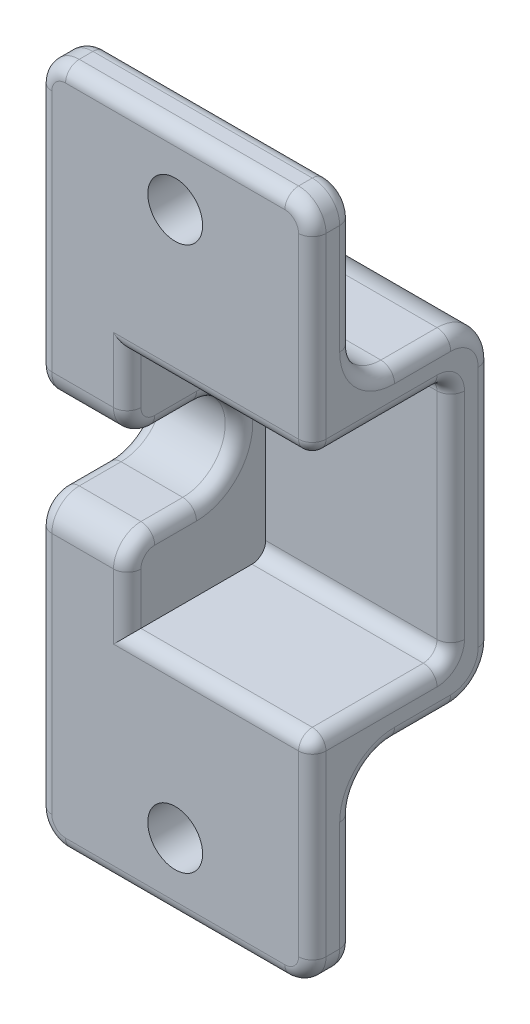
SolidWorks part; units mm, degrees
ref_plane "Front Plane" through (0, 0, 0) normal (0, 0, 1) x (1, 0, 0)
ref_plane "Top Plane" through (0, 0, 0) normal (0, 1, 0) x (1, 0, 0)
ref_plane "Right Plane" through (0, 0, 0) normal (1, 0, 0) x (0, 0, -1)
sketch "Sketch1" plane through (0, 0, 0) normal (1, 0, 0) x (0, 0, -1)
  line L0 (0, 0) -> (3, 0)
  line L1 (3, 0) -> (3, 13)
  line L2 (3, 13) -> (13.1, 13)
  line L3 (13.1, 13) -> (13.1, 36.7)
  line L4 (13.1, 36.7) -> (3, 36.7)
  line L5 (3, 36.7) -> (3, 49.7)
  line L6 (3, 49.7) -> (0, 49.7)
  line L7 (0, 49.7) -> (0, 33.7)
  line L8 (0, 33.7) -> (10.1, 33.7)
  line L9 (10.1, 33.7) -> (10.1, 16)
  line L10 (10.1, 16) -> (0, 16)
  line L11 (0, 16) -> (0, 0)
  point P10 (23.8643, 8.2791)
  point P14 (5.3757, 11.8085)
  dimension "D1" = 17.7
  dimension "D2" = 10.1
  dimension "D3" = 3
  dimension "D4" = 3
  dimension "D5" = 13
  dimension "D6" = 3
extrude "Boss-Extrude1" add sketch "Sketch1" along normal blind 13.5
sketch "Sketch2" plane through (0, 0, 0) normal (-1, 0, 0) x (0, 0, 1)
  line L0 (0, 0) -> (-3, 0)
  line L1 (-3, 0) -> (-3, 13)
  line L2 (-3, 13) -> (-13.1, 13)
  line L3 (-13.1, 13) -> (-13.1, 36.7) construction
  line L4 (-3, 13) -> (-13.1, 13) construction
  line L5 (-13.1, 13) -> (-13.1, 36.7)
  line L6 (-13.1, 36.7) -> (-3, 36.7)
  line L7 (-3, 36.7) -> (-3, 49.7)
  line L8 (-3, 49.7) -> (0, 49.7)
  line L9 (0, 49.7) -> (0, 27.95)
  line L10 (0, 27.95) -> (-5.05, 27.95)
  line L11 (0, 0) -> (0, 21.75)
  line L12 (0, 21.75) -> (-5.05, 21.75)
  line L13 (0, 21.75) -> (0, 27.95) construction
  line L14 (0, 24.85) -> (-10.1, 24.85) construction
  line L15 (-10.1, 33.7) -> (-10.1, 16) construction
  arc A0 (-5.05, 21.75) -> (-5.05, 27.95) centre (-5.05, 24.85) cw
  point P28 (0, 0)
  dimension "D1" = 3.1
extrude "Boss-Extrude2" add sketch "Sketch2" along normal blind 6.5
fillet "Fillet1" radius 3 4 edges at (3.5, 13, -13.1) (3.5, 13, -3) (3.5, 36.7, -13.1) (3.5, 36.7, -3)
fillet "Fillet2" radius 2 6 edges at (13.5, 0, -1.5) (-6.5, 0, -1.5) (-6.5, 49.7, -1.5) (13.5, 49.7, -1.5) (-3.25, 21.75, 0) (-3.25, 27.95, 0)
sketch "Sketch3" plane through (0, 0, -3) normal (0, 0, -1) x (-1, 0, 0)
  line L0 (-3.5, 44.7) -> (-3.5, 5) construction
  line L1 (-3.5, 5) -> (-3.5, 0) construction
  line L2 (-11.5, 0) -> (4.5, 0) construction
  line L3 (-3.5, 44.7) -> (-3.5, 49.7) construction
  line L4 (-11.5, 49.7) -> (4.5, 49.7) construction
  circle A0 centre (-3.5, 5) radius 2
  circle A1 centre (-3.5, 44.7) radius 2
  point P4 (-3, 4.2036)
  dimension "D1" = 4
  dimension "D2" = 5
extrude "Cut-Extrude1" cut sketch "Sketch3" against normal up to surface (3 mm away) up to face at (2.625, 9.3339, 0)
fillet "Fillet3" radius 1 53 edges at (13.5, 9, 0) (12.9142, 0.5858, 0) (3.5, 0, 0) (-5.9142, 0.5858, 0) (-6.5, 10.875, 0) (-6.5, 21.1642, -0.5858) (-6.5, 21.75, -3.525) (-6.5, 24.85, -8.15) (-6.5, 27.95, -3.525) (-6.5, 28.5358, -0.5858) (13.5, 40.7, 0) (12.9142, 49.1142, 0) (3.5, 49.7, 0) (-5.9142, 49.1142, 0) (0, 17.875, 0) (0, 21.1642, -0.5858) (0, 21.75, -3.525) (0, 31.825, 0) (0, 28.5358, -0.5858) (0, 27.95, -3.525) (-6.5, 38.825, 0) (0, 24.85, -8.15) (6.75, 33.7, -10.1) (6.75, 16, 0) (6.75, 16, -10.1) (6.75, 33.7, 0) (13.5, 13.8787, -12.2213) (13.5, 13, -8.05) (13.5, 12.1213, -3.8787) (13.5, 6, -3) (12.9142, 0.5858, -3) (3.5, 0, -3) (-5.9142, 0.5858, -3) (-6.5, 6, -3) (-6.5, 12.1213, -3.8787) (-6.5, 13, -8.05) (-6.5, 13.8787, -12.2213) (-6.5, 24.85, -13.1) (-6.5, 35.8213, -12.2213) (-6.5, 36.7, -8.05) (-6.5, 37.5787, -3.8787) (-6.5, 43.7, -3) (-5.9142, 49.1142, -3) (3.5, 49.7, -3) (12.9142, 49.1142, -3) (13.5, 43.7, -3) (13.5, 37.5787, -3.8787) (13.5, 36.7, -8.05) (13.5, 35.8213, -12.2213) (13.5, 24.85, -13.1) (13.5, 16, -5.05) (13.5, 24.85, -10.1) (13.5, 33.7, -5.05)
